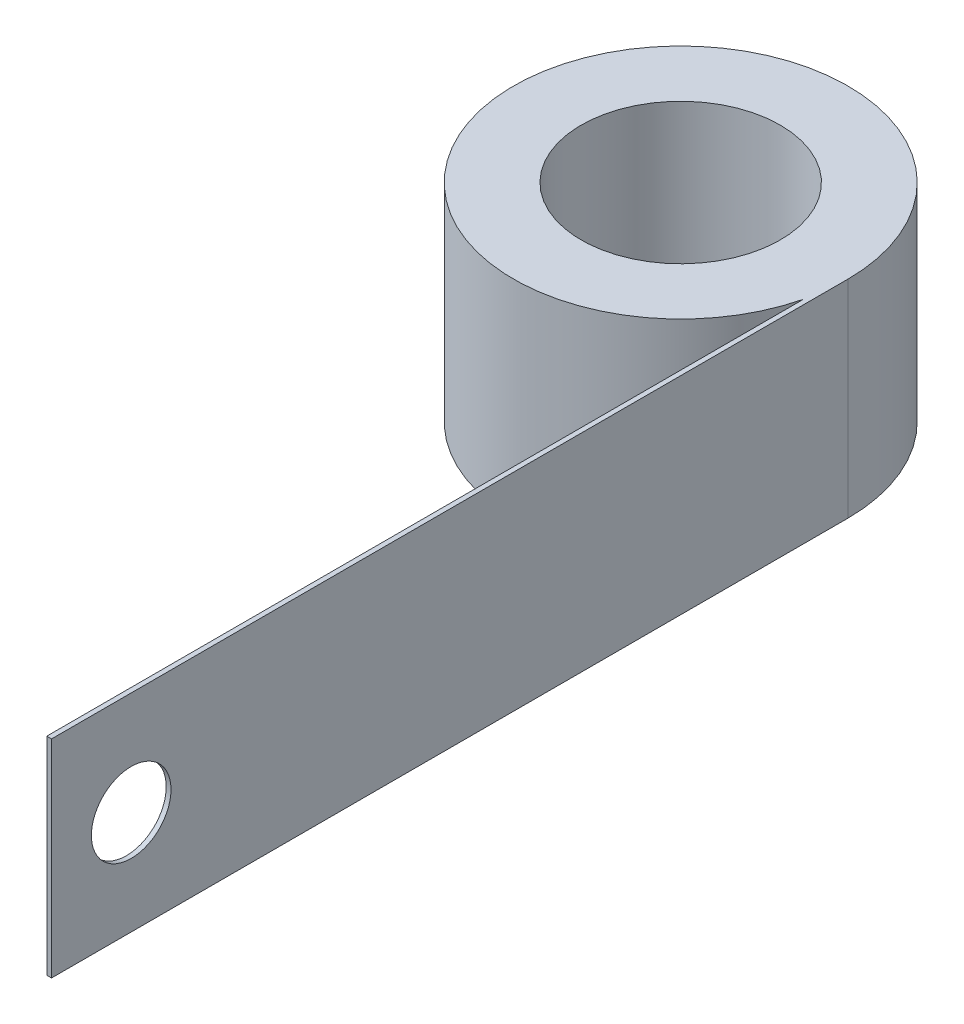
SolidWorks part; units mm, degrees
material "AISI 304"
ref_plane "前视基准面" through (0, 0, 0) normal (0, 0, 1) x (1, 0, 0)
ref_plane "上视基准面" through (0, 0, 0) normal (0, 1, 0) x (1, 0, 0)
ref_plane "右视基准面" through (0, 0, 0) normal (1, 0, 0) x (0, 0, -1)
sketch "草图1" plane through (0, 0, 0) normal (0, 1, 0) x (1, 0, 0)
  circle A0 centre (0, 0) radius 10.5
  circle A1 centre (0, 0) radius 6.25
  dimension "D1" = 12.5
  dimension "D2" = 21
extrude "凸台-拉伸1" add sketch "草图1" along normal blind 13
sketch "草图2" plane through (0, 13, 0) normal (0, 1, 0) x (1, 0, 0)
  line L0 (0, 0) -> (10.5, 0) construction
  line L2 (10.5, 0) -> (10.2, 0)
  line L3 (10.5, 0) -> (10.5, -50)
  line L4 (10.5, -50) -> (10.2, -50)
  line L5 (10.2, 0) -> (10.2, -50)
  circle A0 centre (0, 0) radius 10.5 construction
  dimension "D1" = 0.3
  dimension "D2" = 50
extrude "凸台-拉伸2" add sketch "草图2" against normal up to surface (13 mm away) up to face at (0, 0, 10.5)
sketch "草图3" plane through (10.5, 0, 0) normal (1, 0, 0) x (0, 0, -1)
  line L0 (-45, 6.5) -> (-50, 6.5) construction
  line L1 (-50, 0) -> (-50, 13) construction
  circle A0 centre (-45, 6.5) radius 2.5
  dimension "D1" = 5
  dimension "D2" = 5
extrude "切除-拉伸1" cut sketch "草图3" against normal through all
